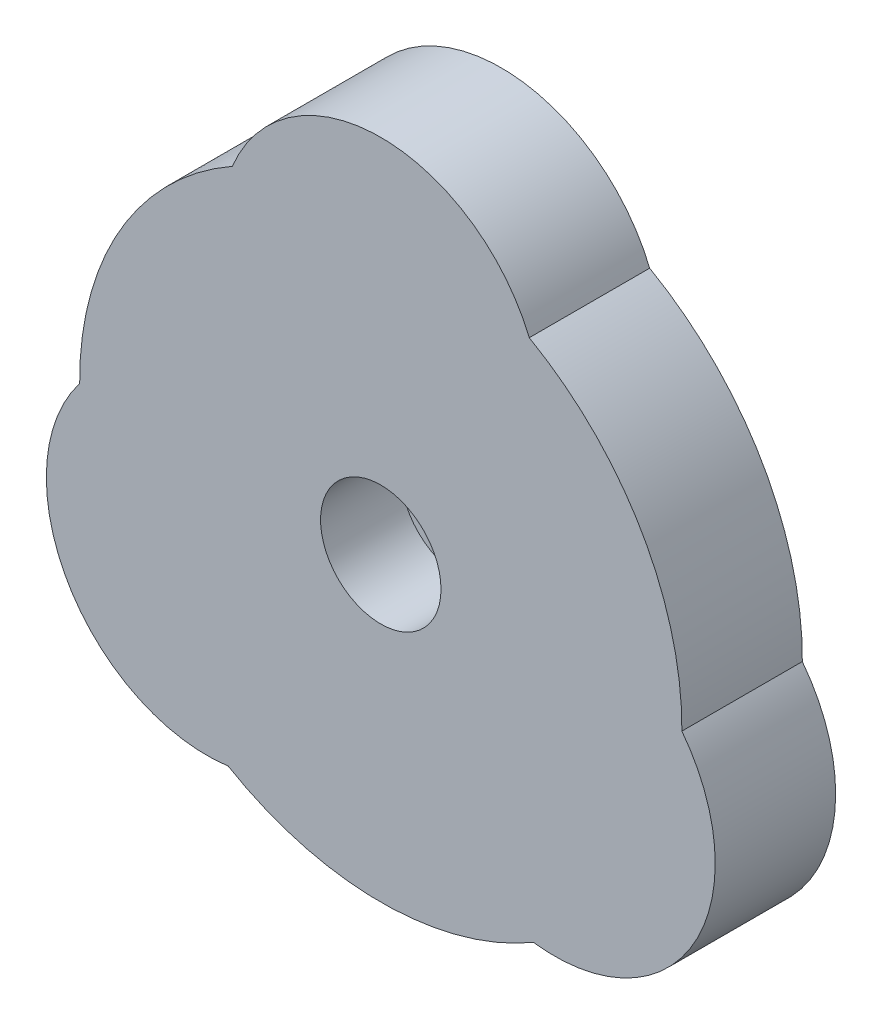
SolidWorks part; units mm, degrees
ref_plane "Plan de face" through (0, 0, 0) normal (0, 0, 1) x (1, 0, 0)
ref_plane "Plan de dessus" through (0, 0, 0) normal (0, 1, 0) x (1, 0, 0)
ref_plane "Plan de droite" through (0, 0, 0) normal (1, 0, 0) x (0, 0, -1)
sketch "Esquisse1" plane through (0, 0, 0) normal (0, 0, 1) x (1, 0, 0)
  circle A0 centre (0, 0) radius 15
  dimension "D1" = 30
extrude "Extrusion1" add sketch "Esquisse1" along normal blind 6
sketch "Esquisse2" plane through (0, 0, 6) normal (0, 0, 1) x (1, 0, 0)
  circle A0 centre (0, 0) radius 3
  dimension "D1" = 6
extrude "Enlèv. mat.-Extru.1" cut sketch "Esquisse2" against normal blind 4
sketch "Esquisse3" plane through (0, 0, 6) normal (0, 0, 1) x (1, 0, 0)
  line L0 (-8, 10) -> (8, 10)
  line L1 (12.6603, 1.9282) -> (4.6603, -11.9282)
  line L2 (-4.6603, -11.9282) -> (-12.6603, 1.9282)
  arc A0 (-8, 10) -> (8, 10) centre (0, 10) cw
  arc A2 (12.6603, 1.9282) -> (4.6603, -11.9282) centre (8.6603, -5) cw
  arc A3 (-4.6603, -11.9282) -> (-12.6603, 1.9282) centre (-8.6603, -5) cw
  dimension "D1" = 10
  dimension "D2" = 8
extrude "Extrusion2" add sketch "Esquisse3" against normal blind 6
